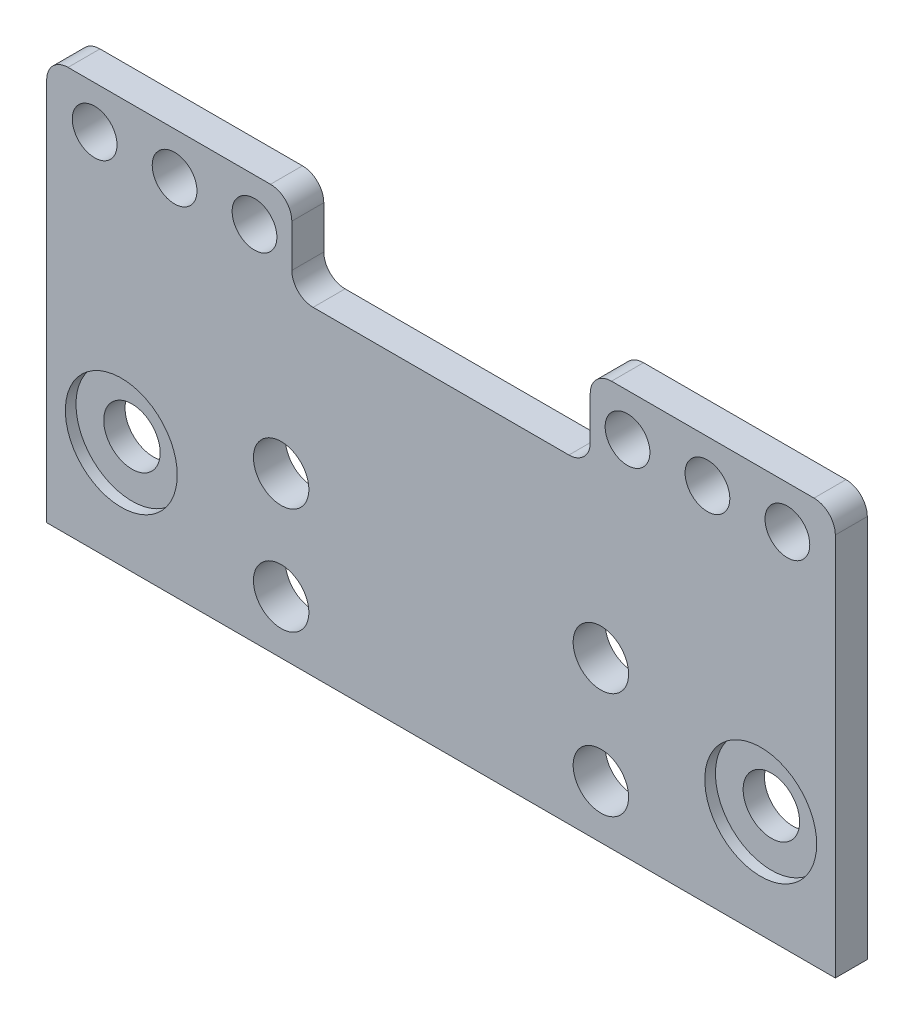
SolidWorks part; units mm, degrees
ref_plane "前视基准面" through (0, 0, 0) normal (0, 0, 1) x (1, 0, 0)
ref_plane "上视基准面" through (0, 0, 0) normal (0, 1, 0) x (1, 0, 0)
ref_plane "右视基准面" through (0, 0, 0) normal (1, 0, 0) x (0, 0, -1)
sketch "草图1" plane through (0, 0, 0) normal (0, 0, 1) x (1, 0, 0)
  line L0 (0, 24) -> (0, 28.3988) construction
  line L1 (14, 20) -> (14, 28)
  line L2 (14, 28) -> (37, 28)
  line L3 (37, 28) -> (37, -10)
  line L4 (37, -10) -> (-37, -10)
  line L5 (-37, -10) -> (-37, 28)
  line L6 (-37, 28) -> (-14, 28)
  line L7 (0, 24) -> (43.6911, 24) construction
  line L8 (-14, 28) -> (-14, 20)
  line L9 (-14, 20) -> (14, 20)
  line L10 (0, 20) -> (0, -29.064) construction
  circle A0 centre (17.5, 24) radius 2.1
  circle A1 centre (25, 24) radius 2.1
  circle A2 centre (32.5, 24) radius 2.1
  circle A3 centre (-32.5, 24) radius 2.1
  circle A4 centre (-17.5, 24) radius 2.1
  circle A5 centre (-25, 24) radius 2.1
  circle A6 centre (30, 0) radius 2.65
  circle A7 centre (-30, 0) radius 2.65
  circle A8 centre (15, 5) radius 2.6
  circle A9 centre (15, -5) radius 2.6
  circle A10 centre (-15, 5) radius 2.6
  circle A11 centre (-15, -5) radius 2.6
  point P0 (0, 0)
  dimension "D1" = 4.2
  dimension "D12" = 60
  dimension "D14" = 5.3
  dimension "D18" = 5.2
  dimension "D19" = 5.2
  dimension "D2" = 35
  dimension "D3" = 50
  dimension "D4" = 65
  dimension "D5" = 74
  dimension "D6" = 37
  dimension "D8" = 14
  dimension "D9" = 8
  dimension "D10" = 4
  dimension "D11" = 34
  dimension "D13" = 30
  dimension "D15" = 20
  dimension "D16" = 5
  dimension "D17" = 5
  dimension "D20" = 15
extrude "凸台-拉伸1" add sketch "草图1" along normal blind 3
fillet "圆角1" radius 2 6 edges at (14, 28, 1.5) (14, 20, 1.5) (-14, 20, 1.5) (-37, 28, 1.5) (37, 28, 1.5) (-14, 28, 1.5)
sketch "草图2" plane through (0, 0, 3) normal (0, 0, 1) x (1, 0, 0)
  circle A0 centre (30, 0) radius 5.25
  circle A1 centre (-30, 0) radius 5.25
  dimension "D1" = 10.5
extrude "切除-拉伸1" cut sketch "草图2" against normal blind 1
